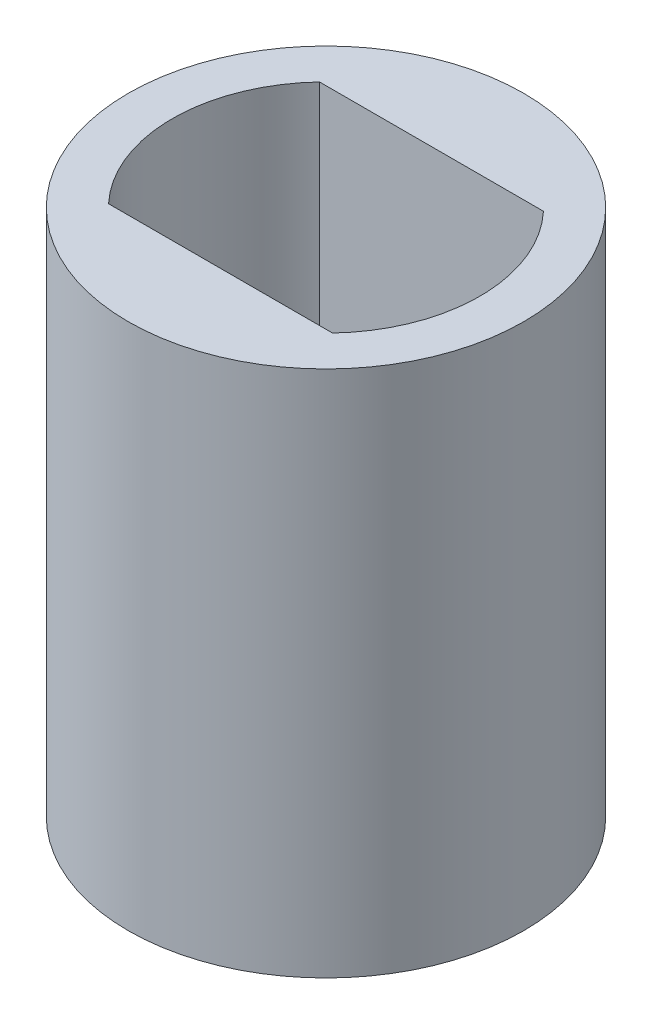
SolidWorks part; units mm, degrees
ref_plane "Спереди" through (0, 0, 0) normal (0, 0, 1) x (1, 0, 0)
ref_plane "Сверху" through (0, 0, 0) normal (0, 1, 0) x (1, 0, 0)
ref_plane "Справа" through (0, 0, 0) normal (1, 0, 0) x (0, 0, -1)
sketch "Эскиз1" plane through (0, 0, 0) normal (0, 1, 0) x (1, 0, 0)
  circle A0 centre (0, 0) radius 4.5
extrude "Вытянуть1" add sketch "Эскиз1" along normal blind 12 from offset 3
sketch "Эскиз2" plane through (0, 15, 0) normal (0, 1, 0) x (1, 0, 0)
  line L0 (0, 0) -> (0, 3.5368) construction
  line L1 (0, 0) -> (2.9273, 0) construction
  line L2 (-2.5475, 2.4) -> (2.5475, 2.4)
  line L3 (-2.5475, -2.4) -> (2.5475, -2.4)
  circle A0 centre (0, 0) radius 3.5 construction
  arc A1 (-2.5475, 2.4) -> (-2.5475, -2.4) centre (0, 0) ccw
  arc A2 (2.5475, 2.4) -> (2.5475, -2.4) centre (0, 0) cw
  dimension "D1" = 2.4
extrude "Вытянуть3" cut sketch "Эскиз2" against normal blind 5
sketch "Эскиз3" plane through (0, 3, 0) normal (0, -1, 0) x (1, 0, 0)
  circle A0 centre (0, 0) radius 2.5
extrude "Вытянуть4" cut sketch "Эскиз3" against normal blind 7
